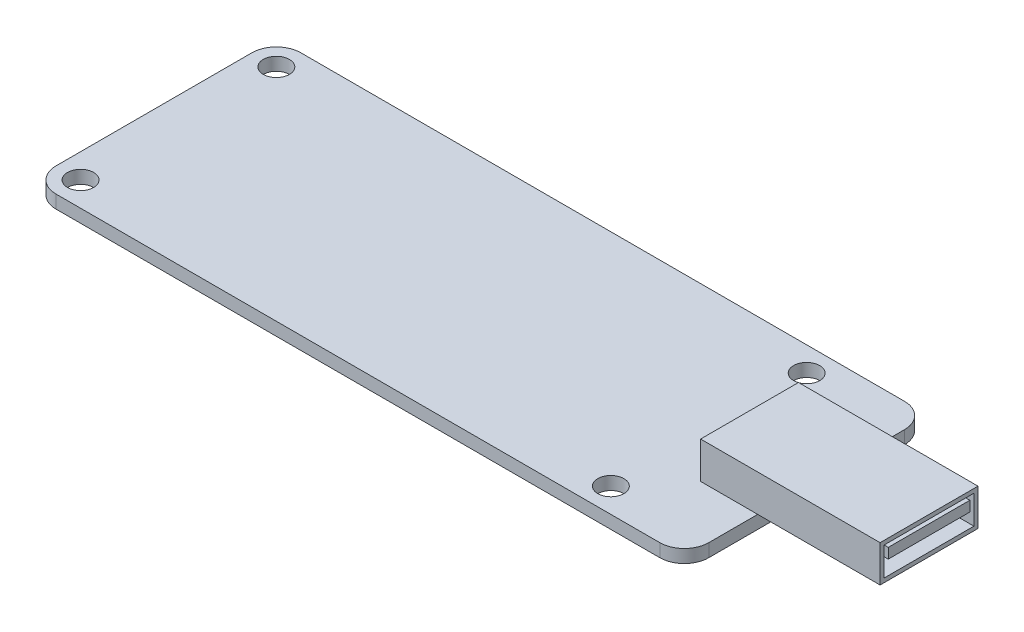
SolidWorks part; units mm, degrees
ref_plane "Front Plane" through (0, 0, 0) normal (0, 0, 1) x (1, 0, 0)
ref_plane "Top Plane" through (0, 0, 0) normal (0, 1, 0) x (1, 0, 0)
ref_plane "Right Plane" through (0, 0, 0) normal (1, 0, 0) x (0, 0, -1)
sketch "PCB_Outline" plane through (0, 0, 0) normal (0, 1, 0) x (1, 0, 0)
  line L1 (-40, 15) -> (40, 15)
  line L2 (-40, 15) -> (-40, -15)
  line L3 (-40, -15) -> (40, -15)
  line L4 (40, 15) -> (40, -15)
  line L5 (-40, 15) -> (40, -15) construction
  line L6 (-40, -15) -> (40, 15) construction
  point P0 (0, 0)
  dimension "D1" = 30
  dimension "D2" = 80
extrude "PCB_Base" add sketch "PCB_Outline" along normal blind 1.6
sketch "Sketch3" plane through (0, 1.6, 0) normal (0, 1, 0) x (1, 0, 0)
  line L0 (40, -15) -> (40, 15) construction
  line L1 (33, 6) -> (55, 6)
  line L2 (33, 6) -> (33, -6)
  line L3 (33, -6) -> (55, -6)
  line L4 (55, 6) -> (55, -6)
  line L5 (-3.355, 0) -> (3.355, 0) construction
  dimension "D1" = 22
  dimension "D2" = 7
  dimension "D3" = 12
  dimension "D4" = 6
extrude "USB_Connecttor_Dummy" add sketch "Sketch3" along normal blind 4.5
sketch "Hole_Locations" plane through (0, 1.6, 0) normal (0, 1, 0) x (1, 0, 0)
  line L0 (40, 15) -> (-40, 15) construction
  line L1 (-40, 15) -> (-40, -15) construction
  line L2 (40, 6) -> (40, 15) construction
  line L3 (-3.355, 0) -> (3.355, 0) construction
  circle A0 centre (-37, 12) radius 1.6
  circle A1 centre (28, 12) radius 1.6
  circle A2 centre (-37, -12) radius 1.6
  circle A3 centre (28, -12) radius 1.6
  dimension "D1" = 3.2
  dimension "D4" = 3.2
  dimension "D2" = 3
  dimension "D3" = 3
  dimension "D5" = 12
extrude "Mounting_Holes" cut sketch "Hole_Locations" against normal through all
sketch "Sketch4" plane through (55, 0, 0) normal (1, 0, 0) x (0, 0, -1)
  line L1 (-5.5, 5.6) -> (5.5, 5.6)
  line L2 (-5.5, 5.6) -> (-5.5, 2.1)
  line L3 (-5.5, 2.1) -> (5.5, 2.1)
  line L4 (5.5, 5.6) -> (5.5, 2.1)
  line L5 (-5, 5.1) -> (5, 5.1)
  line L6 (-5, 5.1) -> (-5, 3.85)
  line L7 (-5, 3.85) -> (5, 3.85)
  line L8 (5, 5.1) -> (5, 3.85)
  line L9 (-6, 6.1) -> (6, 6.1) construction
  line L10 (-6, 1.6) -> (6, 1.6) construction
  line L11 (6, 6.1) -> (6, 1.6) construction
  line L12 (-6, 6.1) -> (-6, 1.6) construction
  dimension "D2" = 0.5
  dimension "D3" = 0.5
  dimension "D4" = 0.5
  dimension "D5" = 0.5
  dimension "D6" = 0.5
  dimension "D7" = 1.25
  dimension "D8" = 0.5
  dimension "D1" = 0.5
extrude "USB_Connector_Dummy_Hole" cut sketch "Sketch4" against normal blind 12
fillet "Fillet1" radius 3 4 edges at (40, 0.8, 15) (40, 0.8, -15) (-40, 0.8, -15) (-40, 0.8, 15)
sketch "Sketch5" plane through (0, 1.6, 0) normal (0, -1, 0) x (1, 0, 0)
  line L0 (55, 6) -> (55, -6) construction
  line L1 (49.5, -3.5) -> (51, -3.5)
  line L2 (49.5, -3.5) -> (49.5, -2)
  line L3 (49.5, -2) -> (51, -2)
  line L4 (51, -3.5) -> (51, -2)
  line L9 (55, -6) -> (40, -6) construction
  line L10 (3.355, 0) -> (-3.355, 0) construction
  line L11 (49.5, 2) -> (51, 2)
  line L12 (49.5, 3.5) -> (51, 3.5)
  line L13 (49.5, 3.5) -> (49.5, 2)
  line L14 (51, 3.5) -> (51, 2)
  dimension "D1" = 1.5
  dimension "D2" = 4
  dimension "D3" = 2.5
extrude "Cut-Extrude1" cut sketch "Sketch5" against normal up to surface (0.5 mm away) up to face at (49, 2.1, 0)
equation "\"PCB_Length\"= 80mm"
equation "\"PCB_Width\"= 30mm"
equation "\"PCB_Thickness\"= 1.6mm"
equation "\"Clearance\"= 0.5mm"
equation "\"Wall_Thickness\"= 2.0mm"
equation "\"Mounting_Hole_Dia\"= 3.2mm"
equation "\"D1@PCB_Outline\" = \"PCB_Width\""
equation "\"D2@PCB_Outline\" = \"PCB_Length\""
equation "\"D1@PCB_Base\" = \"PCB_Thickness\""
equation "\"D1@Hole_Locations\" = \"Mounting_Hole_Dia\""
equation "\"D3@Sketch4\"=\"Clearance\""
equation "\"D4@Sketch4\"=\"Clearance\""
equation "\"D5@Sketch4\"=\"Clearance\""
equation "\"D6@Sketch4\"=\"Clearance\""
equation "\"D8@Sketch4\"=\"Clearance\""
equation "\"D4@Hole_Locations\"=\"Mounting_Hole_Dia\""
equation "\"Hole_Offset_Side\"= 3mm"
equation "\"Hole_Offset_Back\"= 3mm"
equation "\"Hole_Offset_Front\"= 12mm"
equation "\"Boss_ID\"= 2.8mm"
equation "\"Boss_OD\"= 5.6mm"
equation "\"D2@Hole_Locations\"=\"Hole_Offset_Side\""
equation "\"D5@Hole_Locations\"=\"Hole_Offset_Front\""
equation "\"D3@Hole_Locations\"=\"Hole_Offset_Back\""
equation "\"D1@Sketch4\"=\"Clearance\""
